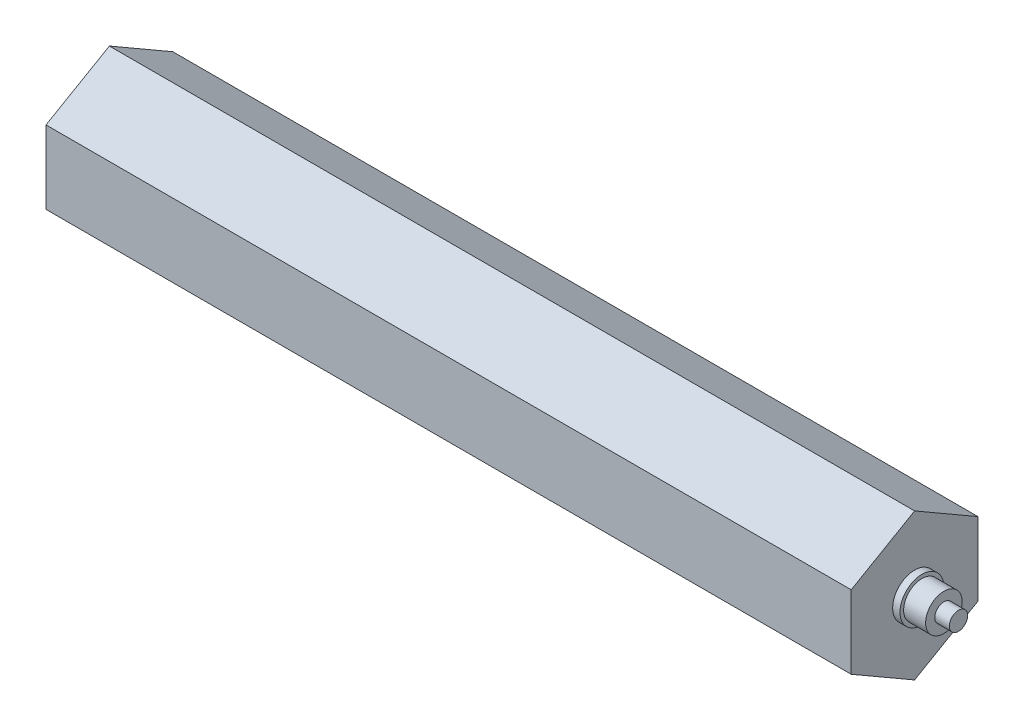
SolidWorks part; units mm, degrees
ref_plane "前视基准面" through (0, 0, 0) normal (0, 0, 1) x (1, 0, 0)
ref_plane "上视基准面" through (0, 0, 0) normal (0, 1, 0) x (1, 0, 0)
ref_plane "右视基准面" through (0, 0, 0) normal (1, 0, 0) x (0, 0, -1)
other "Configuration Table"
sketch "草图1" plane through (0, 0, 0) normal (1, 0, 0) x (0, 0, -1)
  line L1 (17.3205, -10) -> (17.3205, 10)
  line L2 (17.3205, 10) -> (0, 20)
  line L3 (0, 20) -> (-17.3205, 10)
  line L4 (-17.3205, 10) -> (-17.3205, -10)
  line L5 (-17.3205, -10) -> (0, -20)
  line L6 (0, -20) -> (17.3205, -10)
  circle A0 centre (0, 0) radius 17.3205 construction
  dimension "D1" = 20
extrude "凸台-拉伸1" add sketch "草图1" along normal blind 220
sketch "草图2" plane through (220, 0, 0) normal (1, 0, 0) x (0, 0, -1)
  circle A0 centre (0, 0) radius 5
  dimension "D1" = 10
extrude "凸台-拉伸2" add sketch "草图2" along normal blind 8
sketch "草图3" plane through (220, 0, 0) normal (1, 0, 0) x (0, 0, -1)
  circle A2 centre (0, 0) radius 6
  circle A3 centre (0, 0) radius 6
  dimension "D1" = 1
extrude "凸台-拉伸3" add sketch "草图3" along normal blind 2
sketch "草图4" plane through (228, 0, 0) normal (1, 0, 0) x (0, 0, -1)
  circle A0 centre (0, 0) radius 2.5
  dimension "D1" = 5
extrude "凸台-拉伸4" add sketch "草图4" along normal blind 4
